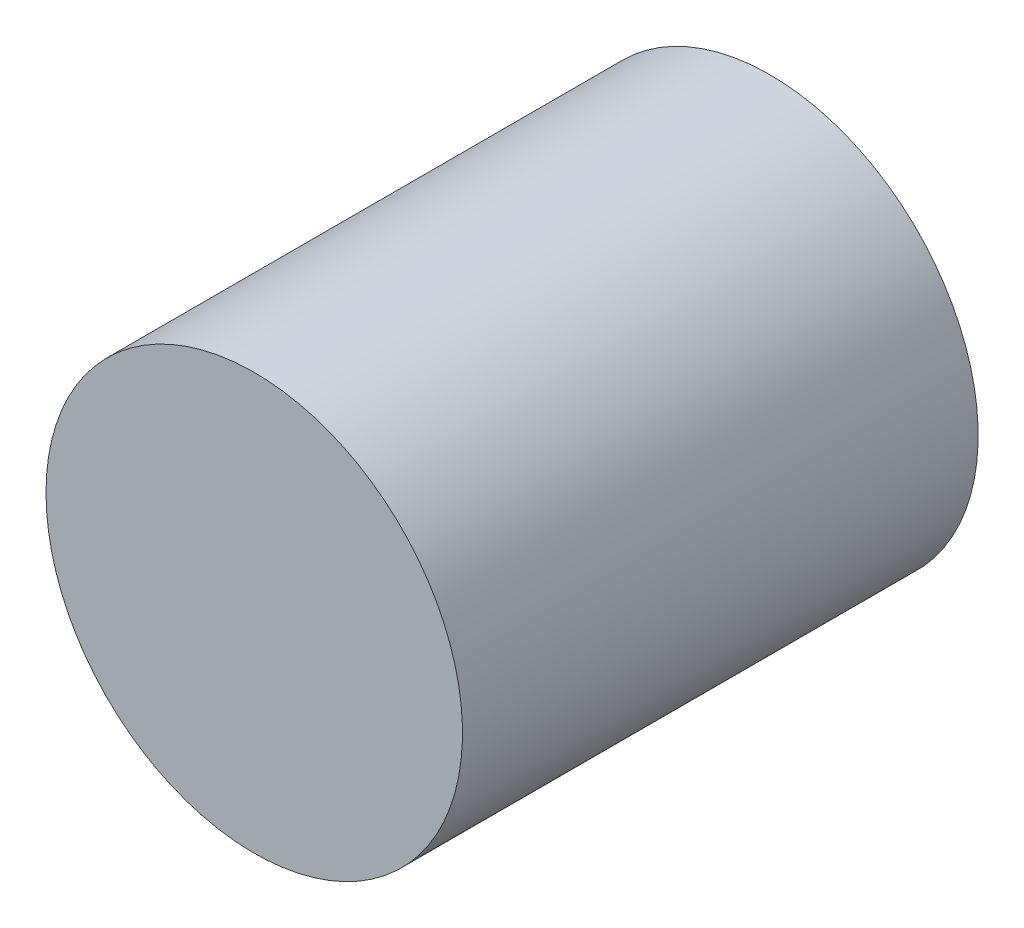
SolidWorks part; units mm, degrees
ref_plane "Front Plane" through (0, 0, 0) normal (0, 0, 1) x (1, 0, 0)
ref_plane "Top Plane" through (0, 0, 0) normal (0, 1, 0) x (1, 0, 0)
ref_plane "Right Plane" through (0, 0, 0) normal (1, 0, 0) x (0, 0, -1)
sketch "Sketch1" plane through (0, 0, 0) normal (0, 0, 1) x (1, 0, 0)
  circle A0 centre (0, 0) radius 21
  dimension "D1" = 42
extrude "Boss-Extrude1" add sketch "Sketch1" along normal blind 52
sketch "Sketch2" plane through (0, 0, 0) normal (0, 0, 1) x (1, 0, 0)
  line L0 (0, 0) -> (0, 26.9084) construction
  circle A0 centre (0, 14.25) radius 2
  circle A1 centre (12.3409, -7.125) radius 2
  circle A2 centre (-12.3409, -7.125) radius 2
  point P3 (0, 14.25)
  point P12 (0, 0)
  dimension "D2" = 4
  dimension "D1" = 14.25
  dimension "D3" = 3
extrude "Boss-Extrude2" add sketch "Sketch2" against normal blind 2.5
